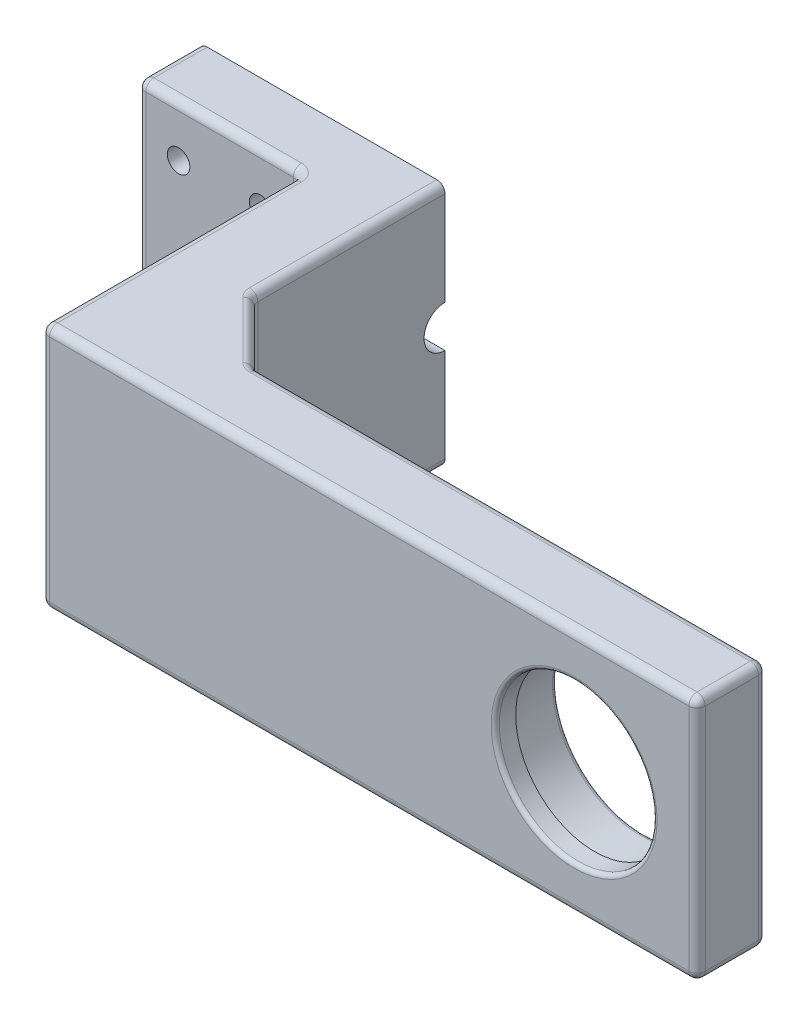
SolidWorks part; units mm, degrees
ref_plane "Front Plane" through (0, 0, 0) normal (0, 0, 1) x (1, 0, 0)
ref_plane "Top Plane" through (0, 0, 0) normal (0, 1, 0) x (1, 0, 0)
ref_plane "Right Plane" through (0, 0, 0) normal (1, 0, 0) x (0, 0, -1)
sketch "Sketch1" plane through (0, 0, 0) normal (0, 0, 1) x (1, 0, 0)
  line L0 (-43.359, 0) -> (46.4553, 0) construction
  line L2 (-30, 30) -> (30, 30)
  line L3 (-30, 30) -> (-30, -30)
  line L4 (-30, -30) -> (30, -30)
  line L5 (30, 30) -> (30, -30)
  line L6 (-30, 30) -> (30, -30) construction
  line L7 (-30, -30) -> (30, 30) construction
  circle A0 centre (0, 0) radius 21.25
  point P3 (0, 0)
  dimension "D1" = 42.5
  dimension "D2" = 60
  dimension "D3" = 60
extrude "Boss-Extrude1" add sketch "Sketch1" along normal blind 12
sketch "Sketch2" plane through (0, 0, 12) normal (0, 0, 1) x (1, 0, 0)
  line L0 (-30, 30) -> (-30, -30) construction
  line L1 (30, 30) -> (-30, 30) construction
  line L2 (-30, 30) -> (-30, -30)
  line L3 (30, 30) -> (-30, 30)
  line L4 (-30, -30) -> (30, -30) construction
  line L5 (30, -30) -> (30, 30) construction
  line L6 (-30, -30) -> (30, -30)
  line L7 (30, -30) -> (30, 30)
  circle A2 centre (0, 0) radius 19.25
  circle A3 centre (0, 0) radius 19.25
  dimension "D1" = 2
extrude "Boss-Extrude2" add sketch "Sketch2" along normal blind 5
sketch "Sketch3" plane through (0, 0, 0) normal (0, 1, 0) x (1, 0, 0)
  line L0 (0, -8.5) -> (-185.6203, -8.5) construction
  line L1 (-30, 0) -> (-110, 0)
  line L2 (-110, 0) -> (-110, 61.5)
  line L3 (-120, -8.5) -> (-120, 96.7953) construction
  line L4 (0, 0) -> (0, -17) construction
  line L5 (30, -17) -> (-30, -17) construction
  line L6 (-30, -17) -> (-130, -17)
  line L7 (-130, -17) -> (-130, 61.5)
  line L8 (-130, 61.5) -> (-110, 61.5)
  line L9 (-30, 0) -> (-30, -17)
  dimension "D1" = 120
  dimension "D2" = 10
  dimension "D3" = 10
  dimension "D4" = 70
extrude "Boss-Extrude3" add sketch "Sketch3" along normal mid plane 60
sketch "Sketch4" plane through (-130, 0, 0) normal (-1, 0, 0) x (0, 0, 1)
  line L0 (-61.5, -30) -> (17, -30) construction
  line L1 (-61.5, 30) -> (-46.5, 30)
  line L2 (-61.5, 30) -> (-61.5, -30)
  line L3 (-61.5, -30) -> (-46.5, -30)
  line L4 (-46.5, 30) -> (-46.5, -30)
  dimension "D1" = 15
extrude "Boss-Extrude4" add sketch "Sketch4" along normal blind 40
sketch "Sketch5" plane through (-170, 0, 0) normal (-1, 0, 0) x (0, 0, 1)
  line L0 (-46.5, 0) -> (-61.5, 0) construction
  line L1 (-46.5, -30) -> (-46.5, 30) construction
  line L2 (-61.5, 30) -> (-61.5, -30) construction
  circle A0 centre (-61.5, 0) radius 5.1
  dimension "D1" = 10.2
extrude "Cut-Extrude1" cut sketch "Sketch5" against normal through all and the other way through all
sketch "Sketch6" plane through (0, 0, -46.5) normal (0, 0, 1) x (1, 0, 0)
  line L0 (-140, 30) -> (-140, -30) construction
  line L1 (-170, 30) -> (-130, 30) construction
  line L2 (-170, -30) -> (-130, -30) construction
  line L3 (-170, 0) -> (-130, 0) construction
  line L4 (-170, -30) -> (-170, 30) construction
  line L5 (-130, 30) -> (-130, -30) construction
  line L6 (-150, 30) -> (-150, -30) construction
  circle A0 centre (-140, 17.5) radius 2.75
  circle A1 centre (-140, -17.5) radius 2.75
  circle A2 centre (-160, -17.5) radius 2.75
  circle A3 centre (-160, 17.5) radius 2.75
  dimension "D1" = 5.5
  dimension "D2" = 20
  dimension "D3" = 35
extrude "Cut-Extrude2" cut sketch "Sketch6" against normal through all
chamfer "Chamfer1" distance 15 angle 45 1 edges at (-110, 0, 0)
fillet "Fillet1" radius 1 1 edges at (21.25, 0, 0)
fillet "Fillet2" radius 1 1 edges at (19.25, 0, 17)
fillet "Fillet3" radius 2 23 edges at (-150, 30, -46.5) (-150, -30, -46.5) (-102.5, 30, -7.5) (-102.5, -30, -7.5) (-130, -30, -14.75) (-130, 30, -14.75) (-130, 0, -46.5) (30, 0, 0) (30, 0, 17) (-50, -30, 17) (-130, 0, 17) (-50, 30, 17) (-110, 30, -38.25) (-110, -30, -38.25) (-110, 0, -15) (-32.5, 30, 0) (-95, 0, 0) (-32.5, -30, 0) (30, -30, 8.5) (30, 30, 8.5) (-170, -30, -54) (-170, 30, -54) (-170, 0, -46.5)
